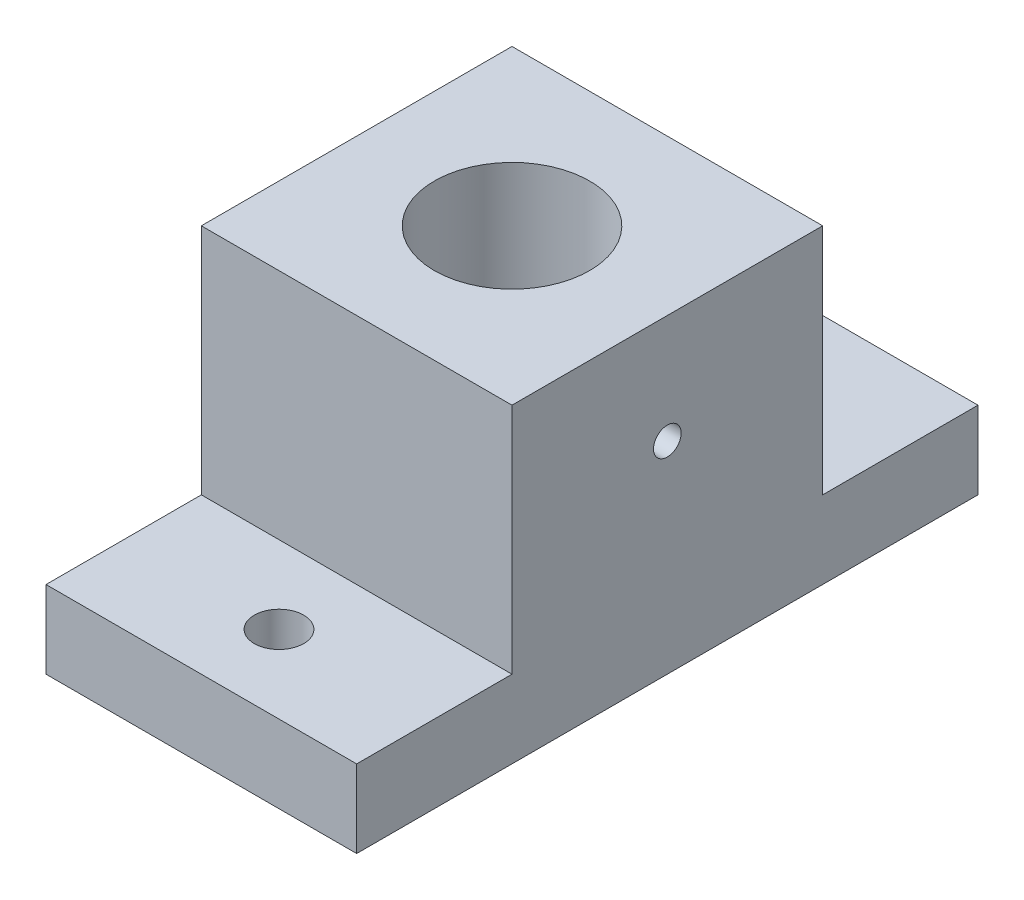
SolidWorks part; units mm, degrees
ref_plane "Front Plane" through (0, 0, 0) normal (0, 0, 1) x (1, 0, 0)
ref_plane "Top Plane" through (0, 0, 0) normal (0, 1, 0) x (1, 0, 0)
ref_plane "Right Plane" through (0, 0, 0) normal (1, 0, 0) x (0, 0, -1)
sketch "Sketch1" plane through (0, 0, 0) normal (0, 1, 0) x (1, 0, 0)
  line L1 (12.7, -25.4) -> (-12.7, -25.4)
  line L2 (12.7, -25.4) -> (12.7, 25.4)
  line L3 (12.7, 25.4) -> (-12.7, 25.4)
  line L4 (-12.7, -25.4) -> (-12.7, 25.4)
  line L5 (12.7, -25.4) -> (-12.7, 25.4) construction
  line L6 (12.7, 25.4) -> (-12.7, -25.4) construction
  point P0 (0, 0)
  dimension "D1" = 25.4
  dimension "D2" = 50.8
extrude "Boss-Extrude1" add sketch "Sketch1" along normal blind 6.35
sketch "Sketch2" plane through (0, 6.35, 0) normal (0, 1, 0) x (1, 0, 0)
  line L0 (-12.7, 25.4) -> (-12.7, -25.4) construction
  line L1 (12.7, -12.7) -> (-12.7, -12.7)
  line L2 (12.7, -12.7) -> (12.7, 12.7)
  line L3 (12.7, 12.7) -> (-12.7, 12.7)
  line L4 (-12.7, -12.7) -> (-12.7, 12.7)
  line L5 (12.7, -12.7) -> (-12.7, 12.7) construction
  line L6 (12.7, 12.7) -> (-12.7, -12.7) construction
  point P0 (0, 0)
  dimension "D1" = 25.4
extrude "Boss-Extrude2" add sketch "Sketch2" along normal blind 19.05
sketch "Sketch3" plane through (0, 25.4, 0) normal (0, 1, 0) x (1, 0, 0)
  circle A0 centre (0, 0) radius 6.35
extrude "Cut-Extrude1" cut sketch "Sketch3" against normal through all
hole_wizard "#10-32 Tapped Hole1" positions "Sketch4" profile "Sketch5" tap size "#10-32" standard "ANSI Inch" end condition through all
sketch "Sketch4" plane through (0, 6.35, 0) normal (0, 1, 0) x (1, 0, 0)
  line L0 (12.7, 25.4) -> (-12.7, 25.4) construction
  line L1 (-12.7, -25.4) -> (12.7, -25.4) construction
  point P0 (0, 19.05)
  point P2 (0, -19.05)
  dimension "D1" = 6.35
  dimension "D2" = 6.35
sketch "Sketch5" plane through (0, 6.35, -19.05) normal (1, 0, 0) x (0, 0, 1)
  line L0 (0, 0) -> (0, 6.35)
  line L1 (0, 6.35) -> (2.0193, 6.35)
  line L2 (2.0193, 6.35) -> (2.0193, 0)
  line L5 (2.0193, 0) -> (0, 0)
  line L11 (0, -6.35) -> (0, 107.95) construction
  dimension "Thru Tap Drill Dia." = 4.0386
  dimension "Thru Tap Drill Depth" = 6.35
cosmetic thread "Hole Thread1" parameters "D2"=4.826
cosmetic thread "Hole Thread2" parameters "D2"=4.826
hole_wizard "#4-40 Tapped Hole1" positions "Sketch7" profile "Sketch8" tap size "#4-40" standard "ANSI Inch"
sketch "Sketch7" plane through (12.7, 0, 0) normal (1, 0, 0) x (0, 0, -1)
  line L0 (-12.7, 25.4) -> (12.7, 25.4) construction
  point P0 (0, 16.51)
  dimension "D1" = 8.89
sketch "Sketch8" plane through (12.7, 16.51, 0) normal (0, 1, 0) x (0, 0, -1)
  line L0 (0, 0) -> (0, 6.35)
  line L1 (0, 6.35) -> (1.1303, 6.35)
  line L2 (1.1303, 6.35) -> (1.1303, 0)
  line L5 (1.1303, 0) -> (0, 0)
  line L11 (0, -6.35) -> (0, 107.95) construction
  dimension "Thru Tap Drill Dia." = 2.2606
  dimension "Thru Tap Drill Depth" = 6.35
cosmetic thread "Hole Thread3" parameters "D2"=2.8448
